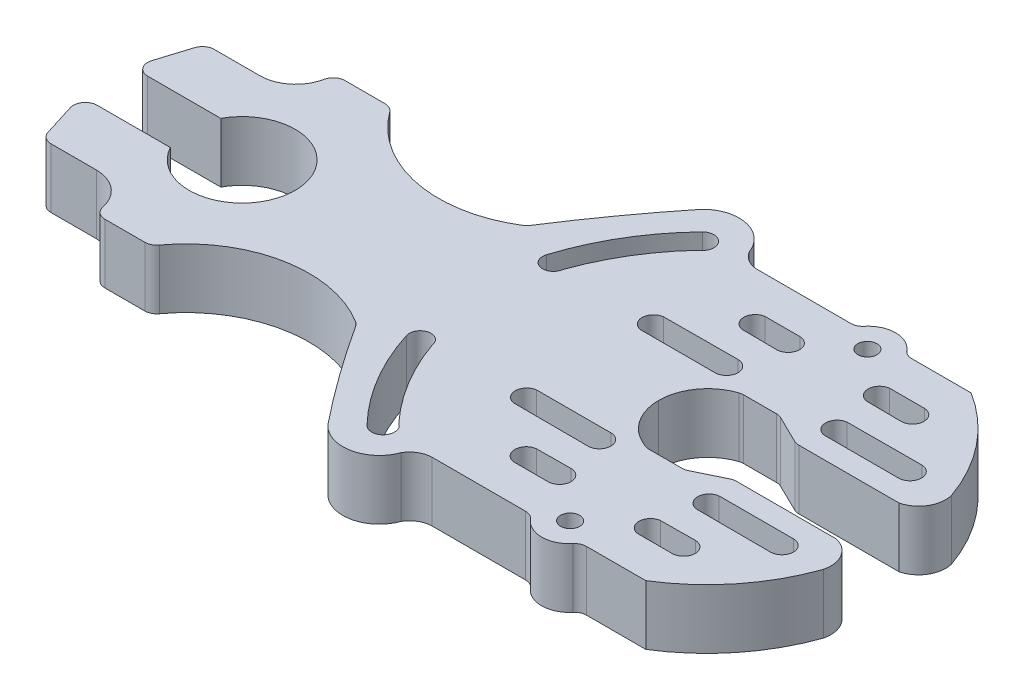
SolidWorks part; units mm, degrees
ref_plane "Front Plane" through (0, 0, 0) normal (0, 0, 1) x (1, 0, 0)
ref_plane "Top Plane" through (0, 0, 0) normal (0, 1, 0) x (1, 0, 0)
ref_plane "Right Plane" through (0, 0, 0) normal (1, 0, 0) x (0, 0, -1)
sketch "Sketch1" plane through (0, 0, 0) normal (0, 1, 0) x (1, 0, 0)
  line L0 (-2771.1564, -1901.5914) -> (-433.7194, -1901.5914) construction
  line L1 (34.0164, 44.6506) -> (112.0164, 44.6506) construction
  line L2 (11.1891, 48.8866) -> (26.1891, 48.8866)
  line L3 (11.1891, 48.8866) -> (14.1513, 58.3667)
  line L4 (14.1513, 58.3667) -> (23.2651, 58.3667)
  line L5 (29.281, 64.8118) -> (38.8809, 64.8118)
  line L6 (139.0799, 49.8972) -> (121.7856, 49.8972)
  line L7 (34.0164, 44.6506) -> (0, 44.6506) construction
  line L8 (109.9698, 52.5862) -> (116.2562, 52.5862)
  line L9 (116.2562, 52.5862) -> (121.7856, 49.8972)
  line L10 (100.7201, 65.7752) -> (106.5363, 65.7752)
  line L11 (100.7201, 61.9613) -> (106.5363, 61.9137)
  line L12 (121.5854, 65.7964) -> (127.4016, 65.7964)
  line L13 (121.5854, 61.9826) -> (127.4016, 61.9349)
  line L14 (92.2203, 53.3915) -> (104.7092, 53.3915)
  line L15 (92.2203, 57.2054) -> (104.7092, 57.2531)
  line L16 (122.9497, 53.4788) -> (135.4386, 53.4788)
  line L17 (122.9497, 57.2927) -> (135.4386, 57.3404)
  line L26 (93.1903, 71.9566) -> (109.9698, 71.9566)
  line L27 (118.078, 71.9566) -> (129.0949, 71.9566)
  line L28 (118.078, 17.3446) -> (129.0949, 17.3446)
  line L29 (93.1903, 17.3446) -> (109.9698, 17.3446)
  line L30 (122.9497, 32.0085) -> (135.4386, 31.9609)
  line L31 (122.9497, 35.8224) -> (135.4386, 35.8224)
  line L32 (92.2203, 32.0958) -> (104.7092, 32.0482)
  line L33 (92.2203, 35.9097) -> (104.7092, 35.9097)
  line L34 (121.5854, 27.3187) -> (127.4016, 27.3663)
  line L35 (121.5854, 23.5048) -> (127.4016, 23.5048)
  line L36 (100.7201, 27.3399) -> (106.5363, 27.3876)
  line L37 (100.7201, 23.526) -> (106.5363, 23.526)
  line L38 (116.2562, 36.715) -> (121.7856, 39.4041)
  line L39 (109.9698, 36.715) -> (116.2562, 36.715)
  line L40 (139.0799, 39.4041) -> (121.7856, 39.4041)
  line L41 (29.281, 24.4895) -> (38.8809, 24.4895)
  line L42 (14.1513, 30.9345) -> (23.2651, 30.9345)
  line L43 (11.1891, 40.4147) -> (14.1513, 30.9345)
  line L44 (11.1891, 40.4147) -> (26.1891, 40.4147)
  arc A0 (26.1891, 40.4147) -> (26.1891, 48.8866) centre (34.0164, 44.6506) ccw
  arc A1 (73.3573, 56.3815) -> (83.1633, 72.8392) centre (112.8166, 44.0209) cw
  arc A2 (73.3573, 56.3815) -> (76.8884, 55.5785) centre (75.0907, 55.8385) ccw
  arc A3 (83.1633, 72.8392) -> (85.4811, 69.8157) centre (84.4876, 71.4543) cw
  arc A4 (85.4811, 69.8157) -> (76.8884, 55.5785) centre (115.1641, 42.1894) ccw
  arc A5 (79.7803, 76.0319) -> (67.5104, 58.9469) centre (232.7465, -46.7717) ccw
  arc A6 (67.5104, 58.9469) -> (38.8809, 64.8118) centre (56.1281, 76.194) cw
  arc A7 (79.7803, 76.0319) -> (89.9421, 73.8941) centre (84.1973, 71.8069) cw
  arc A8 (89.9421, 73.8941) -> (93.1903, 71.9566) centre (93.2884, 75.8126) ccw
  arc A9 (29.281, 64.8118) -> (23.2651, 58.3667) centre (23.265, 64.397) cw
  arc A10 (109.9698, 52.5862) -> (103.9585, 44.6506) centre (112.2308, 44.6289) ccw
  arc A11 (139.0799, 49.8972) -> (142.3654, 55.4096) centre (137.9664, 54.2961) ccw
  arc A12 (109.9698, 71.9566) -> (118.078, 71.9566) centre (114.0239, 69.747) cw
  arc A13 (100.7201, 65.7752) -> (100.7201, 61.9613) centre (100.9409, 63.8683) ccw
  arc A14 (106.5363, 65.7752) -> (106.5363, 61.9137) centre (106.4988, 63.8444) cw
  arc A15 (121.5854, 65.7964) -> (121.5854, 61.9826) centre (121.8062, 63.8895) ccw
  arc A16 (127.4016, 65.7964) -> (127.4016, 61.9349) centre (127.3641, 63.8657) cw
  circle A17 centre (114.0471, 69.608) radius 1.611
  arc A18 (92.2203, 57.2054) -> (92.2203, 53.3915) centre (92.441, 55.2985) ccw
  arc A19 (122.9497, 57.2927) -> (122.9497, 53.4788) centre (123.1704, 55.3858) ccw
  arc A20 (104.7092, 57.2531) -> (104.7092, 53.3915) centre (104.6718, 55.3223) cw
  arc A21 (135.4386, 57.3404) -> (135.4386, 53.4788) centre (135.4012, 55.4096) cw
  arc A31 (129.0949, 71.9566) -> (142.3654, 55.4096) centre (112.2905, 44.8848) cw
  arc A32 (129.0949, 17.3446) -> (142.3654, 33.8916) centre (112.2905, 44.4164) ccw
  arc A33 (135.4386, 31.9609) -> (135.4386, 35.8224) centre (135.4012, 33.8916) ccw
  arc A34 (104.7092, 32.0482) -> (104.7092, 35.9097) centre (104.6718, 33.9789) ccw
  arc A35 (122.9497, 32.0085) -> (122.9497, 35.8224) centre (123.1704, 33.9155) cw
  arc A36 (92.2203, 32.0958) -> (92.2203, 35.9097) centre (92.441, 34.0028) cw
  circle A37 centre (114.0471, 19.6932) radius 1.611
  arc A38 (127.4016, 23.5048) -> (127.4016, 27.3663) centre (127.3641, 25.4356) ccw
  arc A43 (121.5854, 23.5048) -> (121.5854, 27.3187) centre (121.8062, 25.4117) cw
  arc A44 (106.5363, 23.526) -> (106.5363, 27.3876) centre (106.4988, 25.4568) ccw
  arc A45 (100.7201, 23.526) -> (100.7201, 27.3399) centre (100.9409, 25.433) cw
  arc A46 (109.9698, 17.3446) -> (118.078, 17.3446) centre (114.0239, 19.5542) ccw
  arc A47 (139.0799, 39.4041) -> (142.3654, 33.8916) centre (137.9664, 35.0051) cw
  arc A48 (109.9698, 36.715) -> (103.9585, 44.6506) centre (112.2308, 44.6723) cw
  arc A49 (29.281, 24.4895) -> (23.2651, 30.9345) centre (23.265, 24.9042) ccw
  arc A50 (89.9421, 15.4071) -> (93.1903, 17.3446) centre (93.2884, 13.4886) cw
  arc A51 (79.7803, 13.2693) -> (89.9421, 15.4071) centre (84.1973, 17.4943) ccw
  arc A52 (67.5104, 30.3544) -> (38.8809, 24.4895) centre (56.1281, 13.1072) ccw
  arc A53 (79.7803, 13.2693) -> (67.5104, 30.3544) centre (232.7465, 136.0729) cw
  arc A54 (85.4811, 19.4855) -> (76.8884, 33.7227) centre (115.1641, 47.1119) cw
  arc A55 (83.1633, 16.462) -> (85.4811, 19.4855) centre (84.4876, 17.847) ccw
  arc A56 (73.3573, 32.9198) -> (76.8884, 33.7227) centre (75.0907, 33.4627) cw
  arc A57 (73.3573, 32.9198) -> (83.1633, 16.462) centre (112.8166, 45.2803) ccw
  dimension "D2" = 8.9
  dimension "D1" = 78
  dimension "D3" = 15
extrude "Boss-Extrude1" add sketch "Sketch1" along normal blind 10
fillet "Fillet1" radius 2 20 edges at (109.9698, 5, -36.715) (116.2562, 5, -36.715) (121.7856, 5, -39.4041) (121.7856, 5, -49.8972) (109.9698, 5, -52.5862) (116.2562, 5, -52.5862) (118.078, 5, -17.3446) (109.9698, 5, -17.3446) (118.078, 5, -71.9566) (109.9698, 5, -71.9566) (67.5104, 5, -58.9469) (67.5104, 5, -30.3544) (38.8809, 5, -24.4895) (29.281, 5, -24.4895) (38.8809, 5, -64.8118) (29.281, 5, -64.8118) (14.1513, 5, -30.9345) (11.1891, 5, -40.4147) (11.1891, 5, -48.8866) (14.1513, 5, -58.3667)
